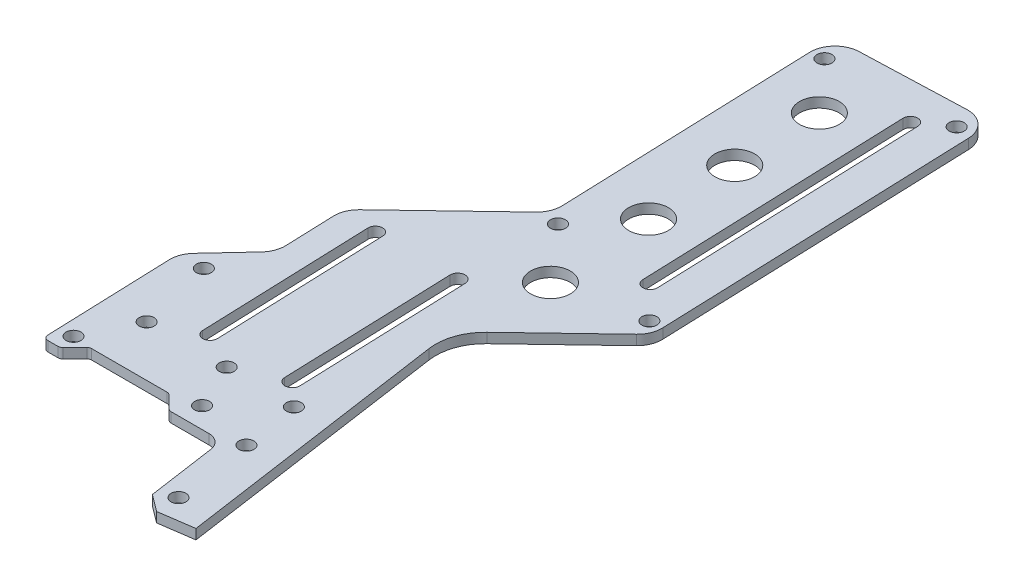
SolidWorks part; units mm, degrees
ref_plane "前视基准面" through (0, 0, 0) normal (0, 0, 1) x (1, 0, 0)
ref_plane "上视基准面" through (0, 0, 0) normal (0, 1, 0) x (1, 0, 0)
ref_plane "右视基准面" through (0, 0, 0) normal (1, 0, 0) x (0, 0, -1)
sketch "Sketch1" plane through (0, 0, 0) normal (0, 1, 0) x (1, 0, 0)
  line L6 (35.9461, 32.5892) -> (55.0686, 50.8364)
  line L7 (56.6136, 54.6329) -> (54.3224, 118.5515)
  line L8 (49.1465, 123.3692) -> (28.1497, 122.6166)
  line L9 (-4.0536, -9.5444) -> (-0.7001, -9.5444)
  line L10 (-0.7001, -9.5444) -> (2.2999, -6.5444)
  line L11 (18.2999, -6.5444) -> (2.2999, -6.5444)
  line L12 (26.2999, -9.5444) -> (21.2999, -9.5444)
  line L13 (18.2999, -6.5444) -> (21.2999, -9.5444)
  line L14 (23.3321, 117.4407) -> (25.1817, 65.8404)
  line L15 (23.6367, 62.044) -> (5.4762, 44.7149)
  line L16 (3.9312, 40.9184) -> (4.2853, 31.0397)
  line L17 (2.9485, 27.454) -> (-3.6599, 20.3542)
  line L18 (-4.9968, 16.7685) -> (-4.0536, -9.5444)
  line L19 (26.2999, -9.5444) -> (28.2999, -9.5444)
  line L20 (28.2999, -9.5444) -> (29.3174, -9.5444)
  line L21 (32.2867, -12.1163) -> (34.2711, -25.8807)
  line L22 (40.206, 3.0407) -> (35.9461, 32.5892)
  line L23 (40.206, 3.0407) -> (44.5979, -27.4229)
  line L24 (44.5979, -27.4229) -> (37.6684, -28.4219)
  line L26 (34.2711, -25.8807) -> (37.6684, -28.4219)
  arc A2 (55.0686, 50.8364) -> (56.6136, 54.6329) centre (51.6168, 54.4537) ccw
  arc A3 (-3.6599, 20.3542) -> (-4.9968, 16.7685) centre (0, 16.9476) ccw
  circle A4 centre (23.7704, -5.3703) radius 1.5
  circle A5 centre (19.5405, 3.8264) radius 1.5
  circle A6 centre (-1.2805, -6.2266) radius 1.5
  circle A7 centre (3.5641, 3.664) radius 1.5
  arc A8 (4.2853, 31.0397) -> (2.9485, 27.454) centre (-0.7115, 30.8606) cw
  arc A9 (5.4762, 44.7149) -> (3.9312, 40.9184) centre (8.928, 41.0975) ccw
  arc A10 (25.1817, 65.8404) -> (23.6367, 62.044) centre (20.1849, 65.6613) cw
  arc A11 (54.3224, 118.5515) -> (49.1465, 123.3692) centre (49.3257, 118.3724) ccw
  arc A12 (28.1497, 122.6166) -> (23.3321, 117.4407) centre (28.3289, 117.6198) ccw
  arc A13 (29.3174, -9.5444) -> (32.2867, -12.1163) centre (29.3174, -12.5444) cw
  dimension "D3" = 3
  dimension "D2" = 135
extrude "Boss-Extrude1" add sketch "Sketch1" along normal blind 2
sketch "Sketch2" plane through (0, 0, 0) normal (0, -1, 0) x (1, 0, 0)
  line L16 (10.9319, -42.3885) -> (12.1697, -7.8569) construction
  line L19 (9.4767, -42.3363) -> (10.7145, -7.8047)
  line L22 (12.3872, -42.4407) -> (13.625, -7.9091)
  line L25 (27.4452, -42.4518) -> (28.683, -7.9202) construction
  line L26 (25.9469, -42.3981) -> (27.1847, -7.8665)
  line L27 (28.9435, -42.5055) -> (30.1813, -7.9739)
  line L32 (45.6918, -115.4691) -> (47.6415, -61.0787) construction
  line L33 (44.2395, -115.4171) -> (46.1892, -61.0266)
  line L34 (47.1441, -115.5212) -> (49.0938, -61.1307)
  arc A16 (9.4767, -42.3363) -> (12.3872, -42.4407) centre (10.9319, -42.3885) ccw
  arc A17 (13.625, -7.9091) -> (10.7145, -7.8047) centre (12.1697, -7.8569) ccw
  arc A18 (25.9469, -42.3981) -> (28.9435, -42.5055) centre (27.4452, -42.4518) ccw
  arc A19 (30.1813, -7.9739) -> (27.1847, -7.8665) centre (28.683, -7.9202) ccw
  arc A24 (44.2395, -115.4171) -> (47.1441, -115.5212) centre (45.6918, -115.4691) ccw
  arc A25 (49.0938, -61.1307) -> (46.1892, -61.0266) centre (47.6415, -61.0787) ccw
  circle A34 centre (34.8935, -107.9094) radius 4
  circle A35 centre (35.5006, -90.2447) radius 4
  circle A36 centre (37.3756, -51.2344) radius 4
  circle A37 centre (36.1937, -72.1788) radius 4
  point P19 (46.6667, -88.2739)
  point P38 (11.5508, -25.1227)
  point P45 (28.0641, -25.186)
  point P75 (30.6759, -3.7668)
extrude "Cut-Extrude1" cut sketch "Sketch2" against normal through all
sketch "Sketch3" plane through (0, 2, 0) normal (0, 1, 0) x (1, 0, 0)
  line L0 (25.9434, 117.8711) -> (27.9394, 62.1871) construction
  line L1 (30.8545, 56.6616) -> (28.7528, 115.2921) construction
  circle A0 centre (0, 18.7605) radius 1.5
  circle A1 centre (54.0546, 54.4882) radius 1.5
  circle A2 centre (25.9434, 117.8711) radius 1.5
  circle A3 centre (51.146, 119.3117) radius 1.5
  circle A4 centre (27.9394, 62.1871) radius 1.5
  circle A5 centre (33.2404, 3.6609) radius 1.5
extrude "Cut-Extrude2" cut sketch "Sketch3" against normal blind 10
fillet "Fillet1" radius 10 1 edges at (35.9461, 1, -32.5892)
sketch "Sketch4" plane through (0, 0, 0) normal (0, -1, 0) x (1, 0, 0)
  arc A4 (36.8062, 22.4407) -> (37.2151, 25.2772) centre (37.4497, 23.7957) ccw
  arc A5 (37.2151, 25.2772) -> (36.8062, 22.4407) centre (37.4497, 23.7957) ccw
  arc A6 (34.9091, 9.282) -> (34.5002, 6.4455) centre (35.1437, 7.8004) ccw
  arc A7 (34.5002, 6.4455) -> (34.9091, 9.282) centre (35.1437, 7.8004) ccw
extrude "Cut-Extrude3" cut sketch "Sketch4" against normal blind 23
fillet "Fillet2" radius 1 5 edges at (21.2999, 1, 9.5444) (18.2999, 1, 6.5444) (2.2999, 1, 6.5444) (-0.7001, 1, 9.5444) (-4.0536, 1, 9.5444)
